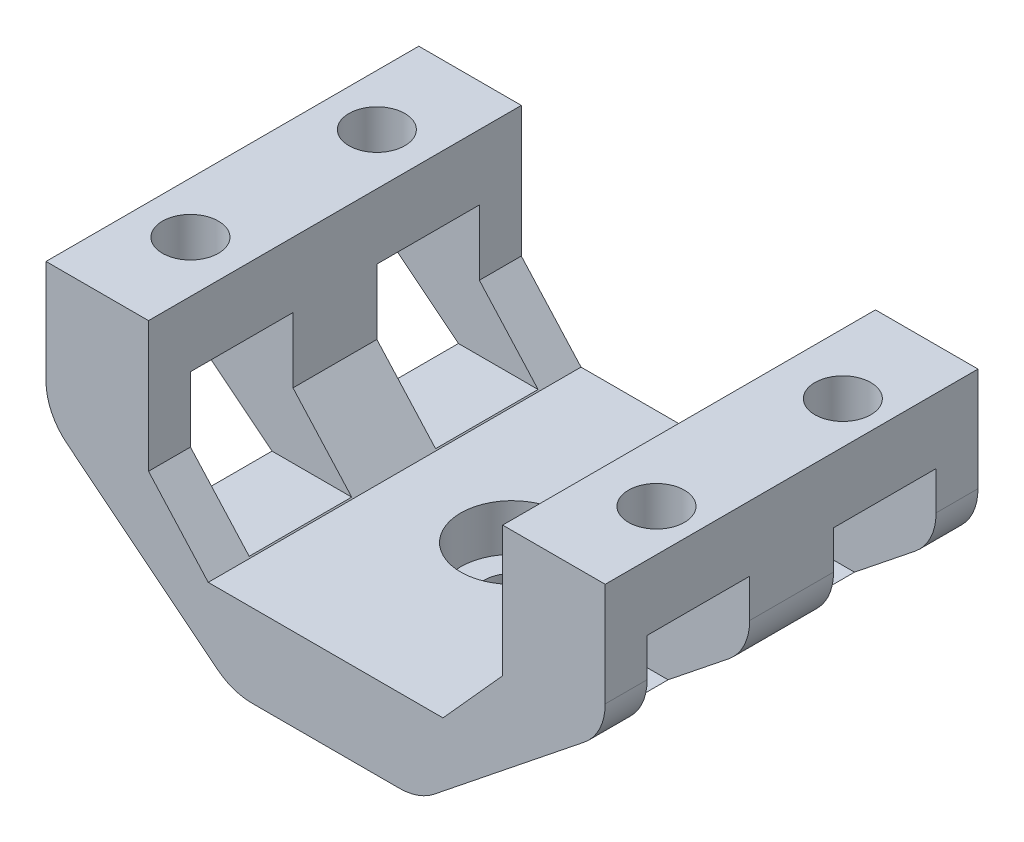
SolidWorks part; units mm, degrees
ref_plane "Alzado" through (0, 0, 0) normal (0, 0, 1) x (1, 0, 0)
ref_plane "Planta" through (0, 0, 0) normal (0, 1, 0) x (1, 0, 0)
ref_plane "Vista lateral" through (0, 0, 0) normal (1, 0, 0) x (0, 0, -1)
sketch "Croquis1" plane through (0, 0, 0) normal (0, 0, 1) x (1, 0, 0)
  line L0 (0, 0) -> (0, -5) construction
  line L21 (0, 0) -> (-4.5, 0) construction
  line L22 (-10, 0) -> (0, -8)
  line L23 (-4.5, 0) -> (-10, 0)
  line L24 (-4.5, 0) -> (-4.5, 7)
  line L25 (-4.5, 7) -> (-10, 7)
  line L26 (-10, 0) -> (-10, 7)
  line L27 (0, -5) -> (10, -5)
  line L28 (0, -5) -> (0, -8)
  line L29 (0, -8) -> (10, -8)
  line L30 (5, -5) -> (5, -8)
  line L31 (0, -5) -> (-4.5, 0)
  line L32 (10, -5) -> (10, -8)
  line L33 (20, 0) -> (10, -8)
  line L34 (10, -5) -> (14.5, 0)
  line L35 (14.5, 7) -> (20, 7)
  line L36 (20, 0) -> (20, 7)
  line L37 (14.5, 0) -> (20, 0)
  line L38 (14.5, 0) -> (14.5, 7)
  dimension "D1" = 7
  dimension "D2" = 4.5
  dimension "D3" = 5
  dimension "D4" = 3
  dimension "D5" = 5
  dimension "D6" = 5.5
extrude "Saliente-Extruir1" add sketch "Croquis1" along normal blind 20 contours L26 L23 L24 L25 | L28 L31 L23 L22 | L30 L27 L28 L29 | L32 L27 L30 L29 | L37 L34 L32 L33 | L38 L37 L36 L35
sketch "Croquis2" plane through (-10, 0, 0) normal (-1, 0, 0) x (0, 0, 1)
  line L0 (10, 7) -> (10, 0) construction
  line L1 (0, 0) -> (0, -8) construction
  line L2 (20, 7) -> (0, 7) construction
  line L3 (20, 0) -> (0, 0) construction
  line L8 (0, 7) -> (10, 7) construction
  line L9 (5, 7) -> (5, 0) construction
  line L15 (17.75, 3.5) -> (12.25, 3.5)
  line L16 (2.25, -3.5) -> (7.75, -3.5)
  line L17 (2.25, -3.5) -> (2.25, 3.5)
  line L18 (2.25, 3.5) -> (7.75, 3.5)
  line L19 (7.75, -3.5) -> (7.75, 3.5)
  line L20 (2.25, -3.5) -> (7.75, 3.5) construction
  line L21 (2.25, 3.5) -> (7.75, -3.5) construction
  line L22 (12.25, -3.5) -> (12.25, 3.5)
  line L23 (17.75, -3.5) -> (12.25, -3.5)
  line L24 (17.75, -3.5) -> (17.75, 3.5)
  dimension "D1" = 5.5
  dimension "D2" = 3.5
extrude "Cortar-Extruir3" cut sketch "Croquis2" against normal through all
sketch "Croquis3" plane through (0, 7, 0) normal (0, 1, 0) x (1, 0, 0)
  line L0 (-7.25, 0) -> (-7.25, -5) construction
  line L1 (-4.5, 0) -> (-10, 0) construction
  circle A0 centre (-7.25, -5) radius 1.5
  circle A1 centre (17.75, -5) radius 1.5
  circle A2 centre (17.75, -15) radius 1.5
  circle A3 centre (-7.25, -15) radius 1.5
  dimension "D1" = 3
  dimension "D2" = 2
  dimension "D3" = 2
extrude "Cortar-Extruir4" cut sketch "Croquis3" against normal through all
fillet "Redondeo1" radius 3 8 edges at (10, -8, 10) (20, 0, 1.125) (20, 0, 18.875) (20, 0, 10) (0, -8, 10) (-10, 0, 18.875) (-10, 0, 1.125) (-10, 0, 10)
sketch "Croquis4" plane through (0, -5, 0) normal (0, 1, 0) x (1, 0, 0)
  line L0 (5, 0) -> (5, -20) construction
  line L1 (0, 0) -> (10, 0) construction
  line L2 (0, -20) -> (10, -20) construction
  circle A0 centre (5, -10) radius 1.5
extrude "Cortar-Extruir5" cut sketch "Croquis4" against normal through all
sketch "Croquis8" plane through (0, 0, 0) normal (0, 0, -1) x (-1, 0, 0)
  line L0 (0, -5) -> (-10, -5) construction
  line L1 (1.2969, -5) -> (-11.2969, -5)
  line L2 (-5, -5) -> (-5, -3.559)
  line L3 (1.2969, -3.559) -> (-11.2969, -3.559)
  line L4 (-11.2969, -5) -> (-11.2969, -3.559)
  line L5 (-10, -5) -> (-14.5, 0) construction
  line L6 (1.2969, -5) -> (1.2969, -3.559)
  line M14 (4.5, 0) -> (0, -5)
  line M15 (0, -5) -> (-10, -5)
  line M16 (-10, -5) -> (-14.5, 0)
extrude "Saliente-Extruir2" add sketch "Croquis8" against normal through all contours L3 L2 M14 M15 | L2 L3 L1 M16
sketch "Croquis9" plane through (0, -3.559, 0) normal (0, 1, 0) x (1, 0, 0)
  line L0 (5, 0) -> (5, -20) construction
  line L1 (-1.2969, 0) -> (11.2969, 0) construction
  line L2 (-1.2969, -20) -> (11.2969, -20) construction
  circle A0 centre (5, -10) radius 2.75
  dimension "D1" = 5.5
extrude "Cortar-Extruir6" cut sketch "Croquis9" against normal blind 2.5
